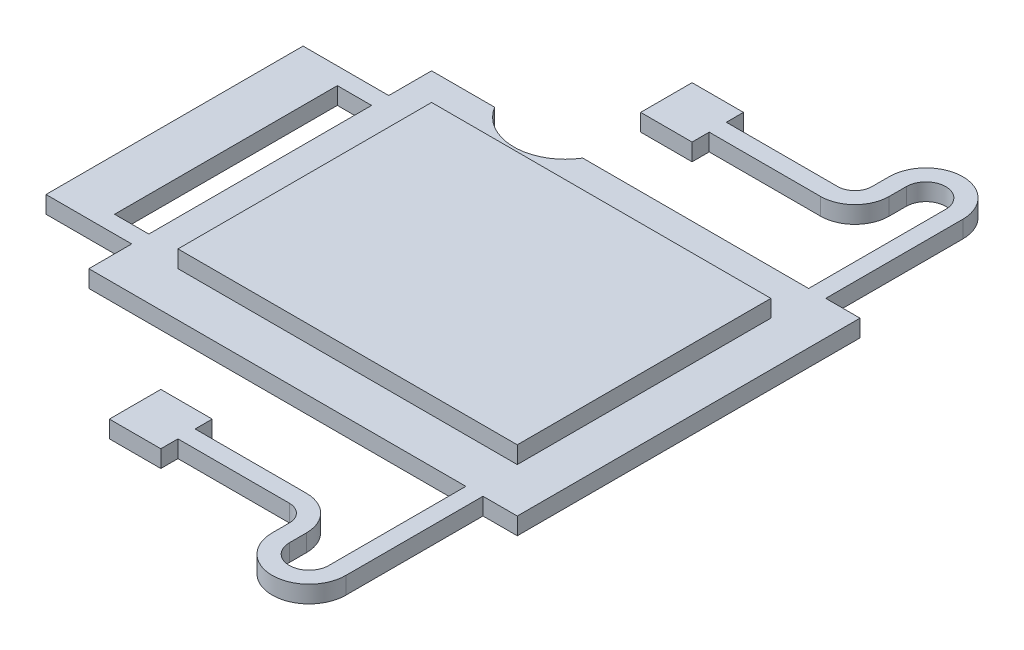
SolidWorks part; units mm, degrees
material "PLA"
ref_plane "Спереди" through (0, 0, 0) normal (0, 0, 1) x (1, 0, 0)
ref_plane "Сверху" through (0, 0, 0) normal (0, 1, 0) x (1, 0, 0)
ref_plane "Справа" through (0, 0, 0) normal (1, 0, 0) x (0, 0, -1)
sketch "Эскиз1" plane through (0, 0, 0) normal (0, 1, 0) x (1, 0, 0)
  line L1 (12.5, 10) -> (-12.5, 10)
  line L2 (12.5, 10) -> (12.5, -10)
  line L3 (12.5, -10) -> (-12.5, -10)
  line L4 (-12.5, 10) -> (-12.5, -10)
  line L5 (12.5, 10) -> (-12.5, -10) construction
  line L6 (12.5, -10) -> (-12.5, 10) construction
  point P0 (0, 0)
  dimension "D1" = 25
  dimension "D2" = 20
extrude "Бобышка-Вытянуть1" add sketch "Эскиз1" along normal blind 1
sketch "Эскиз3" plane through (0, 0, 0) normal (0, 1, 0) x (1, 0, 0)
  line L0 (0, 0) -> (-50000, 0) construction
  line L1 (-12.5, 10) -> (-12.5, -10) construction
  line L6 (-14.5, 7.5) -> (-17.5, 7.5)
  line L7 (-14.5, 6.5) -> (-14.5, -6.5)
  line L8 (-14.5, -7.5) -> (-17.5, -7.5)
  line L9 (-17.5, 7.5) -> (-17.5, -7.5)
  line L10 (-14.5, 7.5) -> (-17.5, -7.5) construction
  line L11 (-14.5, -7.5) -> (-17.5, 7.5) construction
  line L12 (-14.5, 7.5) -> (-12.5, 7.5)
  line L13 (-12.5, 7.5) -> (-12.5, 6.5)
  line L14 (-12.5, 6.5) -> (-14.5, 6.5)
  line L15 (-12.5, -6.5) -> (-14.5, -6.5)
  line L16 (-12.5, -7.5) -> (-12.5, -6.5)
  line L17 (-14.5, -7.5) -> (-12.5, -7.5)
  line L18 (-14.5, 7.5) -> (-14.5, 6.5) construction
  point P3 (-16, 0)
  dimension "D1" = 3
  dimension "D2" = 15
  dimension "D3" = 2
  dimension "D4" = 1
extrude "Бобышка-Вытянуть2" add sketch "Эскиз3" along normal blind 1
sketch "Эскиз4" plane through (0, 0, 0) normal (0, 1, 0) x (1, 0, 0)
  line L0 (0, 0) -> (50000, 0) construction
  line L1 (9.5, 10) -> (9.5, 18)
  line L2 (12.5, 10) -> (-12.5, 10) construction
  line L3 (7.2, 18) -> (7.2, 17)
  line L4 (5.2, 15) -> (-1.3, 15)
  line L5 (10.5, 10) -> (10.5, 18)
  line L6 (6.2, 18) -> (6.2, 17)
  line L7 (5.2, 16) -> (-1.3, 16)
  line L8 (10.5, 10) -> (9.5, 10)
  line L9 (-1.3, 16) -> (-1.3, 15) construction
  line L10 (-4.3, 14) -> (-1.3, 14)
  line L11 (-4.3, 14) -> (-4.3, 17)
  line L12 (-1.3, 14) -> (-1.3, 15)
  line L13 (-4.3, 17) -> (-1.3, 17)
  line L14 (-4.3, 14) -> (-1.3, 17) construction
  line L15 (-1.3, 14) -> (-4.3, 17) construction
  line L16 (-1.3, 16) -> (-1.3, 17)
  line L17 (-1.3, 15.5) -> (-2.8, 15.5) construction
  line L18 (12.5, -10) -> (12.5, 10) construction
  line L19 (-4.3, -14) -> (-4.3, -17)
  line L20 (-4.3, -17) -> (-1.3, -17)
  line L21 (-1.3, -16) -> (-1.3, -17)
  line L22 (5.2, -16) -> (-1.3, -16)
  line L23 (6.2, -18) -> (6.2, -17)
  line L24 (10.5, -10) -> (10.5, -18)
  line L25 (10.5, -10) -> (9.5, -10)
  line L26 (9.5, -10) -> (9.5, -18)
  line L27 (7.2, -18) -> (7.2, -17)
  line L28 (5.2, -15) -> (-1.3, -15)
  line L29 (-1.3, -14) -> (-1.3, -15)
  line L30 (-4.3, -14) -> (-1.3, -14)
  arc A0 (9.5, 18) -> (7.2, 18) centre (8.35, 18) ccw
  arc A1 (7.2, 17) -> (5.2, 15) centre (5.2, 17) cw
  arc A2 (10.5, 18) -> (6.2, 18) centre (8.35, 18) ccw
  arc A3 (6.2, 17) -> (5.2, 16) centre (5.2, 17) cw
  arc A4 (6.2, -17) -> (5.2, -16) centre (5.2, -17) ccw
  arc A5 (10.5, -18) -> (6.2, -18) centre (8.35, -18) cw
  arc A6 (9.5, -18) -> (7.2, -18) centre (8.35, -18) cw
  arc A7 (7.2, -17) -> (5.2, -15) centre (5.2, -17) ccw
  point P22 (-2.8, 15.5)
  dimension "D4" = 2.15
  dimension "D5" = 2
  dimension "D1" = 1
  dimension "D2" = 3
  dimension "D3" = 3
  dimension "D6" = 1
  dimension "D7" = 6.5
  dimension "D8" = 8
  dimension "D9" = 2
extrude "Бобышка-Вытянуть3" add sketch "Эскиз4" along normal blind 1
sketch "Эскиз5" plane through (0, 1, 0) normal (0, 1, 0) x (1, 0, 0)
  line L1 (9.9, 7.4) -> (-9.9, 7.4)
  line L2 (9.9, 7.4) -> (9.9, -7.4)
  line L3 (9.9, -7.4) -> (-9.9, -7.4)
  line L4 (-9.9, 7.4) -> (-9.9, -7.4)
  line L5 (9.9, 7.4) -> (-9.9, -7.4) construction
  line L6 (9.9, -7.4) -> (-9.9, 7.4) construction
  point P0 (0, 0)
  dimension "D1" = 19.8
  dimension "D2" = 14.8
extrude "Бобышка-Вытянуть4" add sketch "Эскиз5" along normal blind 1
sketch "Эскиз6" plane through (0, 0, 0) normal (0, -1, 0) x (1, 0, 0)
  circle A0 centre (0, 0) radius 2
  dimension "D1" = 4
extrude "Вырез-Вытянуть2" cut sketch "Эскиз6" against normal blind 1.6
sketch "Эскиз7" plane through (0, 0, 0) normal (0, -1, 0) x (1, 0, 0)
  line L0 (9.5, -10) -> (-12.5, -10) construction
  line L1 (-12.5, -10) -> (-12.5, -7.5) construction
  circle A0 centre (-6.25, -11.55) radius 3
  point P4 (0, 0)
  dimension "D3" = 6
  dimension "D1" = 1.55
  dimension "D2" = 6.25
extrude "Вырез-Вытянуть3" cut sketch "Эскиз7" against normal up to surface (1 mm away) up to face at (1.7011, 1, 0)
